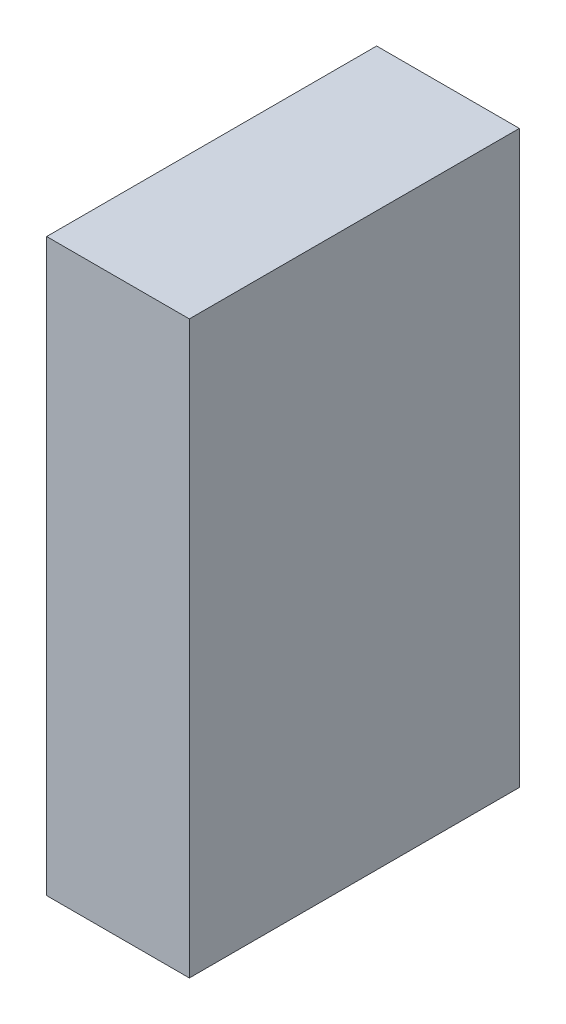
SolidWorks part; units mm, degrees
material "Pine"
ref_plane "Front Plane" through (0, 0, 0) normal (0, 0, 1) x (1, 0, 0)
ref_plane "Top Plane" through (0, 0, 0) normal (0, 1, 0) x (1, 0, 0)
ref_plane "Right Plane" through (0, 0, 0) normal (1, 0, 0) x (0, 0, -1)
sketch "Sketch1" plane through (0, 0, 0) normal (0, 1, 0) x (1, 0, 0)
  line L1 (19.05, -44.0531) -> (-19.05, -44.0531)
  line L2 (19.05, -44.0531) -> (19.05, 44.0531)
  line L3 (19.05, 44.0531) -> (-19.05, 44.0531)
  line L4 (-19.05, -44.0531) -> (-19.05, 44.0531)
  line L5 (19.05, -44.0531) -> (-19.05, 44.0531) construction
  line L6 (19.05, 44.0531) -> (-19.05, -44.0531) construction
  point P0 (0, 0)
  dimension "D1" = 38.1
  dimension "D2" = 88.1063
extrude "Boss-Extrude1" add sketch "Sketch1" along normal up to surface (152.4 mm away)
